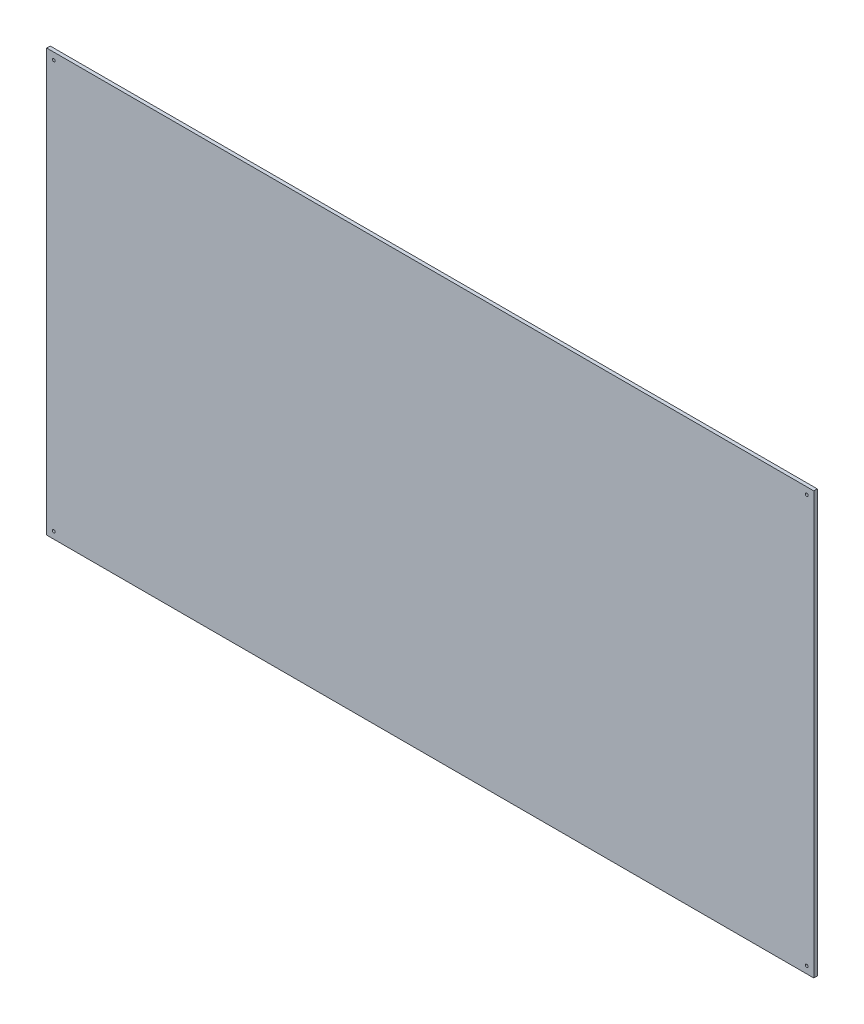
SolidWorks part; units mm, degrees
ref_plane "前视基准面" through (0, 0, 0) normal (0, 0, 1) x (1, 0, 0)
ref_plane "上视基准面" through (0, 0, 0) normal (0, 1, 0) x (1, 0, 0)
ref_plane "右视基准面" through (0, 0, 0) normal (1, 0, 0) x (0, 0, -1)
sketch "草图1" plane through (0, 0, 0) normal (0, 0, 1) x (1, 0, 0)
  line L1 (-1100, 605) -> (1100, 605)
  line L2 (-1100, 605) -> (-1100, -605)
  line L3 (-1100, -605) -> (1100, -605)
  line L4 (1100, 605) -> (1100, -605)
  dimension "D1" = 2200
  dimension "D2" = 1210
  dimension "D3" = 1100
  dimension "D4" = 605
extrude "凸台-拉伸1" add sketch "草图1" along normal blind 10
sketch "草图2" plane through (0, 0, 10) normal (0, 0, 1) x (1, 0, 0)
  line L0 (1100, 605) -> (-1100, 605) construction
  line L1 (-1100, 605) -> (-1100, -605) construction
  line L2 (0, -5.5) -> (0, 5.5) construction
  line L4 (5.5, 0) -> (-5.5, 0) construction
  circle A0 centre (-1080, 585) radius 4.05
  circle A1 centre (1080, 585) radius 4.05
  circle A2 centre (1080, -585) radius 4.05
  circle A3 centre (-1080, -585) radius 4.05
  point P2 (0, 0)
  dimension "D1" = 20
  dimension "D2" = 20
extrude "切除-拉伸1" cut sketch "草图2" against normal blind 10
